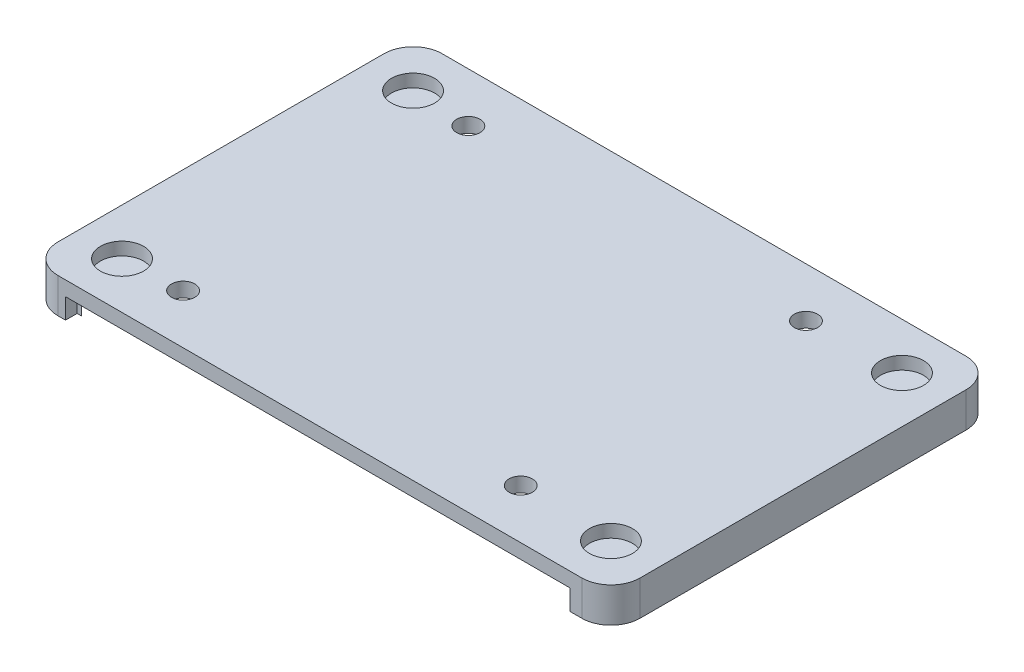
SolidWorks part; units mm, degrees
ref_plane "Front Plane" through (0, 0, 0) normal (0, 0, 1) x (1, 0, 0)
ref_plane "Top Plane" through (0, 0, 0) normal (0, 1, 0) x (1, 0, 0)
ref_plane "Right Plane" through (0, 0, 0) normal (1, 0, 0) x (0, 0, -1)
sketch "Sketch1" plane through (0, 0, 0) normal (0, 1, 0) x (1, 0, 0)
  line L1 (5, 0) -> (95, 0)
  line L2 (0, 5) -> (0, 61)
  line L3 (5, 66) -> (95, 66)
  line L4 (100, 5) -> (100, 61)
  arc A0 (0, 61) -> (5, 66) centre (5, 61) cw
  arc A1 (95, 66) -> (100, 61) centre (95, 61) cw
  arc A2 (95, 0) -> (100, 5) centre (95, 5) ccw
  arc A3 (5, 0) -> (0, 5) centre (5, 5) cw
  point P7 (0, 66)
  point P12 (100, 0)
  point P15 (0, 0)
  dimension "D3" = 5
  dimension "D1" = 66
  dimension "D2" = 100
extrude "Boss-Extrude2" add sketch "Sketch1" along normal blind 6 contours L2 A0 L3 A1 L4 A2 L1 A3
sketch "Sketch2" plane through (0, 0, 0) normal (0, -1, 0) x (1, 0, 0)
  line L0 (5, 0) -> (95, 0) construction
  line L1 (7, -2) -> (93, -2)
  line L2 (2, -7) -> (2, -59)
  line L3 (7, -64) -> (93, -64)
  line L4 (98, -7) -> (98, -59)
  line L5 (0, -5) -> (0, -61) construction
  line L6 (5, -66) -> (95, -66) construction
  line L7 (100, -5) -> (100, -61) construction
  arc A0 (93, -64) -> (98, -59) centre (93, -59) ccw
  arc A1 (93, -2) -> (98, -7) centre (93, -7) cw
  arc A2 (2, -59) -> (7, -64) centre (7, -59) ccw
  arc A3 (7, -2) -> (2, -7) centre (7, -7) ccw
  dimension "D5" = 5
  dimension "D1" = 2
  dimension "D2" = 2
  dimension "D3" = 2
  dimension "D4" = 2
extrude "Cut-Extrude1" cut sketch "Sketch2" against normal blind 3.5
sketch "Sketch5" plane through (0, 6, 0) normal (0, 1, 0) x (1, 0, 0)
  line L0 (0, 5) -> (0, 61) construction
  line L1 (5, 66) -> (95, 66) construction
  line L2 (5, 0) -> (95, 0) construction
  line L3 (100, 5) -> (100, 61) construction
  circle A0 centre (8, 58) radius 3.7
  circle A1 centre (8, 8) radius 3.7
  circle A2 centre (92, 58) radius 3.7
  circle A3 centre (92, 8) radius 3.7
  dimension "D1" = 7.4
  dimension "D2" = 8
  dimension "D5" = 8
  dimension "D6" = 7.4
  dimension "D7" = 7.4
  dimension "D8" = 8
  dimension "D10" = 8
  dimension "D11" = 8
  dimension "D12" = 7.4
  dimension "D3" = 8
  dimension "D4" = 8
  dimension "D9" = 8
extrude "Cut-Extrude2" cut sketch "Sketch5" against normal blind 2.2
sketch "Sketch6" plane through (0, 6, 0) normal (0, 1, 0) x (1, 0, 0)
  line L0 (5, 0) -> (95, 0) construction
  line L1 (100, 5) -> (100, 61) construction
  circle A0 centre (18, 57.5) radius 2
  circle A1 centre (18, 8.5) radius 2
  circle A2 centre (76, 57.5) radius 2
  circle A3 centre (76, 8.5) radius 2
  dimension "D1" = 49
  dimension "D2" = 8.5
  dimension "D3" = 58
  dimension "D4" = 58
  dimension "D5" = 24
extrude "Cut-Extrude3" cut sketch "Sketch6" against normal through all
sketch "Sketch11" plane through (0, 0, 0) normal (0, -1, 0) x (-1, 0, 0)
  line L0 (-5, 0) -> (-95, 0) construction
  line L1 (0, 5) -> (-2.4174, 5)
  line L2 (0, 5) -> (0, 61)
  line L3 (0, 61) -> (-2.4174, 61)
  line L4 (-2.4174, 5) -> (-2.4174, 61)
  line L5 (-93, 2) -> (-6.2908, 2)
  line L6 (-93, 2) -> (-93, 0)
  line L7 (-93, 0) -> (-6.2908, 0)
  line L8 (-6.2908, 2) -> (-6.2908, 0)
  arc A0 (-2, 59) -> (-7, 64) centre (-7, 59) ccw construction
extrude "Cut-Extrude7" cut sketch "Sketch11" against normal blind 3.5
